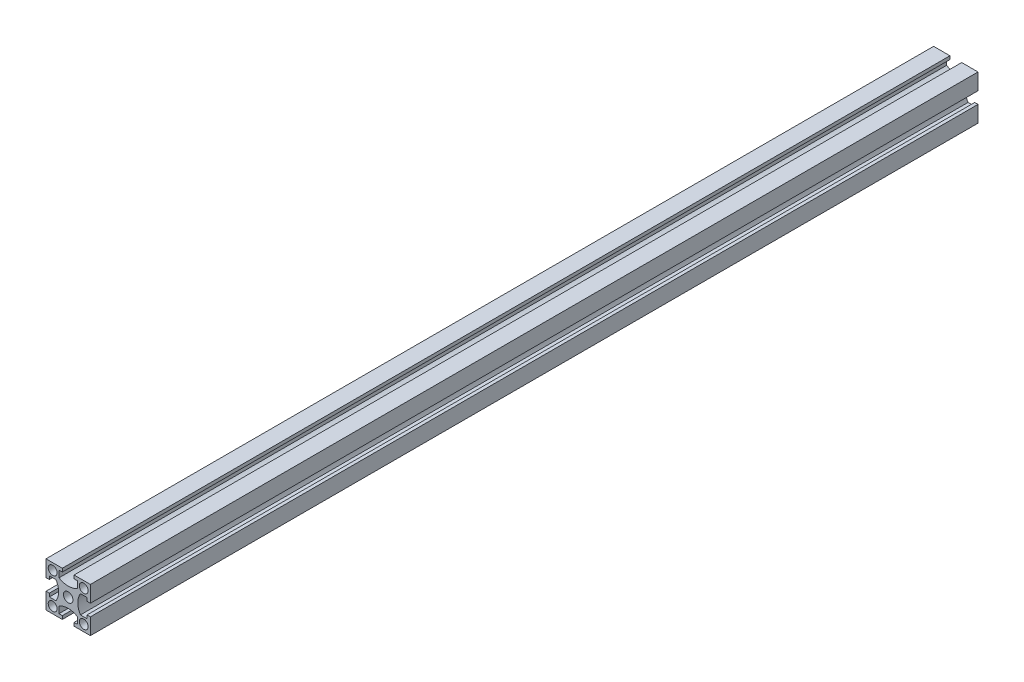
SolidWorks part; units mm, degrees
material "6061-T6 (SS)"
ref_plane "정면" through (0, 0, 0) normal (0, 0, 1) x (1, 0, 0)
ref_plane "윗면" through (0, 0, 0) normal (0, 1, 0) x (1, 0, 0)
ref_plane "우측면" through (0, 0, 0) normal (1, 0, 0) x (0, 0, -1)
sketch "스케치1" plane through (0, 0, 0) normal (0, 0, 1) x (1, 0, 0)
  line L1 (-10, 10) -> (10, 10)
  line L2 (-10, 10) -> (-10, -10)
  line L3 (-10, -10) -> (10, -10)
  line L4 (10, 10) -> (10, -10)
  line L5 (-10, 10) -> (10, -10) construction
  line L6 (-10, -10) -> (10, 10) construction
  point P0 (0, 0)
  dimension "D1" = 20
  dimension "D2" = 20
extrude "보스-돌출1" add sketch "스케치1" along normal blind 400
sketch "스케치2" plane through (0, 0, 400) normal (0, 0, 1) x (1, 0, 0)
  line L0 (-2.65, 10) -> (-2.65, 8.5)
  line L1 (10, 10) -> (-10, 10) construction
  line L2 (-2.65, 8.5) -> (-4.15, 8.5)
  line L3 (-4.15, 8.5) -> (-4.15, 5.5)
  line L4 (-2.65, 10) -> (2.65, 10)
  line L5 (2.65, 10) -> (2.65, 8.5)
  line L6 (2.65, 8.5) -> (4.15, 8.5)
  line L7 (4.15, 8.5) -> (4.15, 5.5)
  line L8 (10, 2.65) -> (8.5, 2.65)
  line L9 (8.5, 2.65) -> (8.5, 4.15)
  line L10 (8.5, 4.15) -> (5.5, 4.15)
  line L11 (10, 2.65) -> (10, -2.65)
  line L12 (10, -2.65) -> (8.5, -2.65)
  line L13 (8.5, -2.65) -> (8.5, -4.15)
  line L14 (8.5, -4.15) -> (5.5, -4.15)
  line L15 (2.65, -10) -> (2.65, -8.5)
  line L16 (2.65, -8.5) -> (4.15, -8.5)
  line L17 (4.15, -8.5) -> (4.15, -5.5)
  line L18 (2.65, -10) -> (-2.65, -10)
  line L19 (-2.65, -10) -> (-2.65, -8.5)
  line L20 (-2.65, -8.5) -> (-4.15, -8.5)
  line L21 (-4.15, -8.5) -> (-4.15, -5.5)
  line L22 (-10, -2.65) -> (-8.5, -2.65)
  line L23 (-8.5, -2.65) -> (-8.5, -4.15)
  line L24 (-8.5, -4.15) -> (-5.5, -4.15)
  line L25 (-10, -2.65) -> (-10, 2.65)
  line L26 (-10, 2.65) -> (-8.5, 2.65)
  line L27 (-8.5, 2.65) -> (-8.5, 4.15)
  line L28 (-8.5, 4.15) -> (-5.5, 4.15)
  arc A1 (-4.15, 5.5) -> (4.15, 5.5) centre (0, 12.3394) ccw
  arc A2 (5.5, 4.15) -> (5.5, -4.15) centre (12.3394, 0) ccw
  arc A3 (4.15, -5.5) -> (-4.15, -5.5) centre (0, -12.3394) ccw
  arc A4 (-5.5, -4.15) -> (-5.5, 4.15) centre (-12.3394, 0) ccw
  circle A5 centre (0, 0) radius 2.15
  circle A6 centre (-7, 7) radius 2
  circle A7 centre (7, 7) radius 2
  circle A8 centre (7, -7) radius 2
  circle A9 centre (-7, -7) radius 2
  point P4 (-2.65, 9.25)
  point P43 (0, 0)
  dimension "D2" = 1.5
  dimension "D8" = 4.3
  dimension "D9" = 4
  dimension "D10" = 4
  dimension "D11" = 4
  dimension "D12" = 4
  dimension "D21" = 8
  dimension "D1" = 5.3
  dimension "D3" = 8.3
  dimension "D4" = 4.15
  dimension "D5" = 2.65
  dimension "D6" = 4
  dimension "D7" = 3
  dimension "D13" = 14
  dimension "D14" = 7
  dimension "D15" = 7
  dimension "D16" = 7
  dimension "D17" = 14
  dimension "D18" = 7
  dimension "D19" = 7
  dimension "D20" = 7
extrude "컷-돌출1" cut sketch "스케치2" against normal through all
